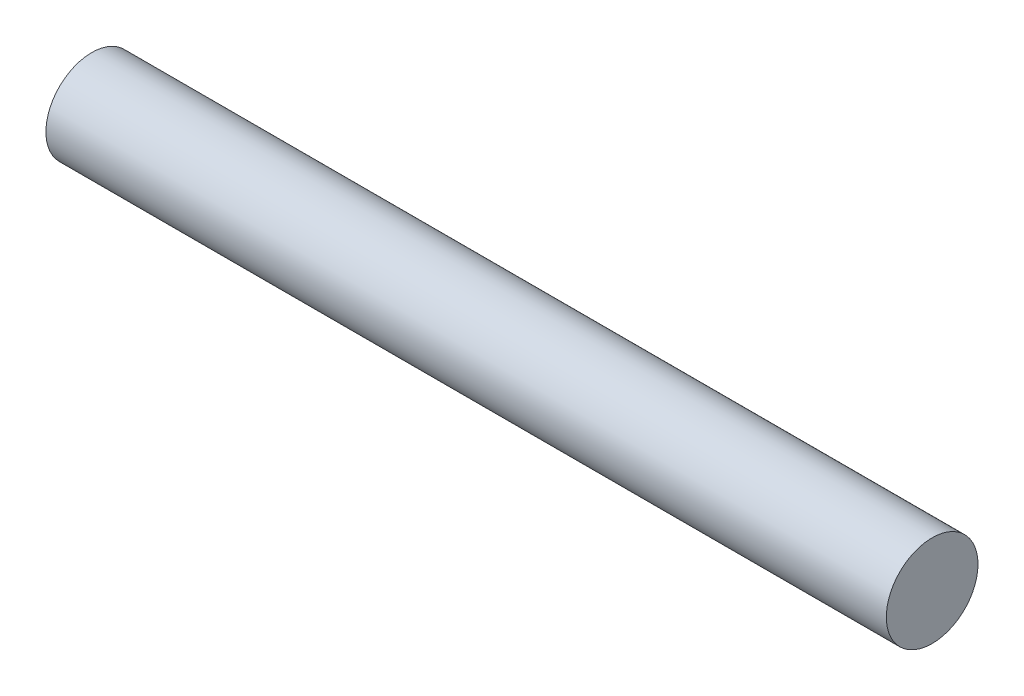
SolidWorks part; units mm, degrees
ref_plane "Front Plane" through (0, 0, 0) normal (0, 0, 1) x (1, 0, 0)
ref_plane "Top Plane" through (0, 0, 0) normal (0, 1, 0) x (1, 0, 0)
ref_plane "Right Plane" through (0, 0, 0) normal (1, 0, 0) x (0, 0, -1)
sketch "Sketch1" plane through (0, 0, 0) normal (1, 0, 0) x (0, 0, -1)
  circle A0 centre (0, 0) radius 3
  dimension "D1" = 6
extrude "Boss-Extrude1" add sketch "Sketch1" along normal blind 55
